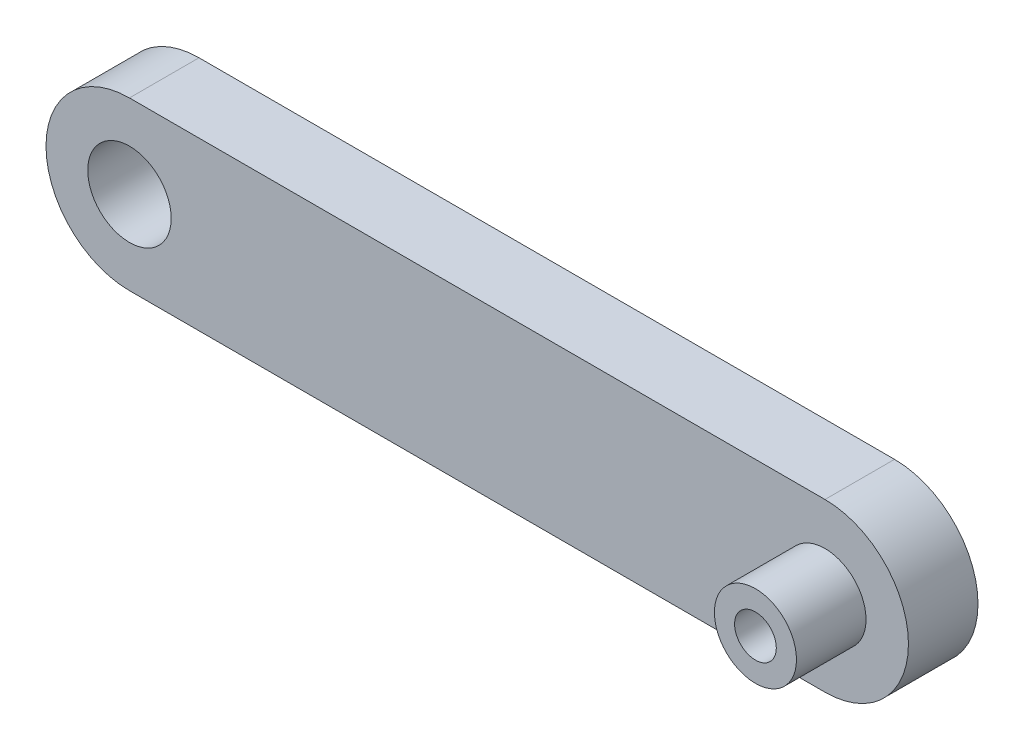
SolidWorks part; units mm, degrees
ref_plane "Front Plane" through (0, 0, 0) normal (0, 0, 1) x (1, 0, 0)
ref_plane "Top Plane" through (0, 0, 0) normal (0, 1, 0) x (1, 0, 0)
ref_plane "Right Plane" through (0, 0, 0) normal (1, 0, 0) x (0, 0, -1)
sketch "Sketch1" plane through (0, 0, 0) normal (0, 0, 1) x (1, 0, 0)
  line L0 (-25, 0) -> (25, 0) construction
  line L1 (-25, 6) -> (25, 6)
  line L2 (-25, -6) -> (25, -6)
  arc A0 (-25, 6) -> (-25, -6) centre (-25, 0) ccw
  arc A1 (25, -6) -> (25, 6) centre (25, 0) ccw
  circle A2 centre (25, 0) radius 1.5
  circle A3 centre (-25, 0) radius 3
  point P2 (0, 0)
  dimension "D2" = 6
  dimension "D3" = 6
  dimension "D4" = 3
  dimension "D1" = 50
extrude "Boss-Extrude1" add sketch "Sketch1" along normal blind 5
sketch "Sketch2" plane through (0, 0, 5) normal (0, 0, 1) x (1, 0, 0)
  circle A0 centre (25, 0) radius 1.5 construction
  circle A1 centre (25, 0) radius 1.5
  circle A2 centre (25, 0) radius 2.95
  dimension "D1" = 5.9
extrude "Boss-Extrude2" add sketch "Sketch2" along normal blind 5
